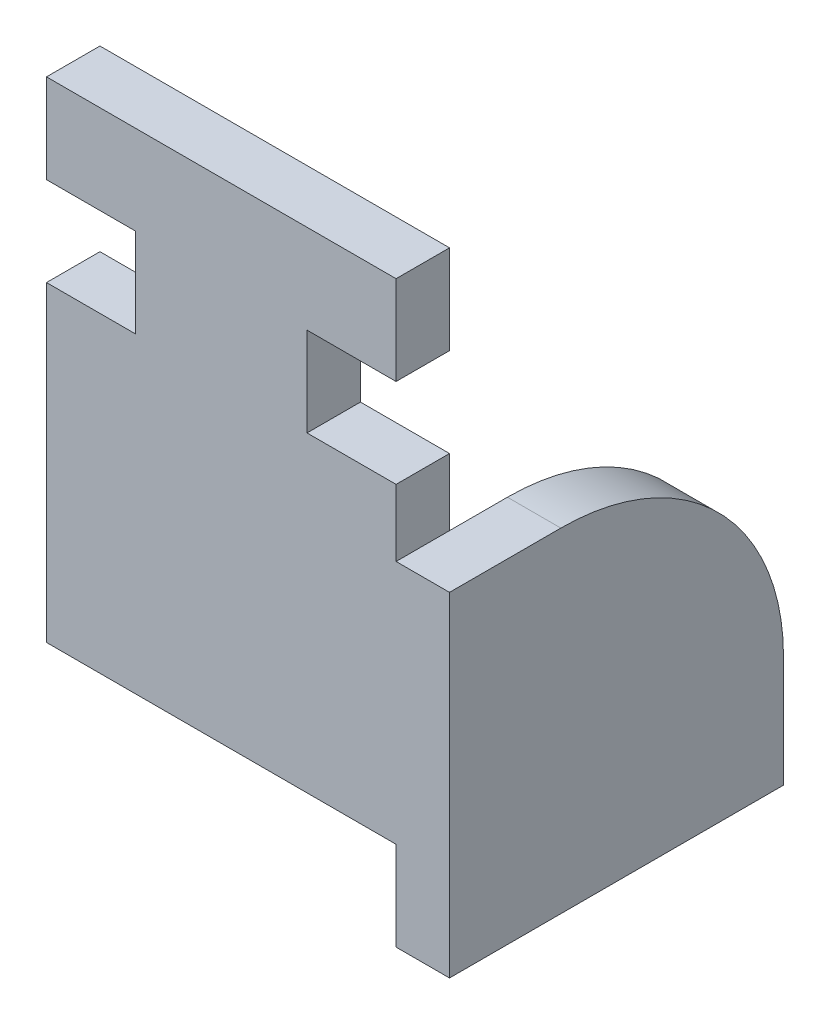
SolidWorks part; units mm, degrees
material "PBT General Purpose"
ref_plane "Front Plane" through (0, 0, 0) normal (0, 0, 1) x (1, 0, 0)
ref_plane "Top Plane" through (0, 0, 0) normal (0, 1, 0) x (1, 0, 0)
ref_plane "Right Plane" through (0, 0, 0) normal (1, 0, 0) x (0, 0, -1)
sketch "Sketch1" plane through (0, 0, 0) normal (0, 0, 1) x (1, 0, 0)
  line L0 (0, 0) -> (0, 1.4)
  line L1 (0, 1.4) -> (0.4, 1.4)
  line L2 (0.4, 1.4) -> (0.4, 1.8)
  line L3 (0.4, 1.8) -> (0, 1.8)
  line L4 (0, 1.8) -> (0, 2.2)
  line L5 (0, 2.2) -> (1.57, 2.2)
  line L6 (1.57, 2.2) -> (1.57, 1.8)
  line L7 (1.57, 1.8) -> (1.17, 1.8)
  line L8 (1.17, 1.8) -> (1.17, 1.4)
  line L9 (1.17, 1.4) -> (1.57, 1.4)
  line L10 (1.57, 1.4) -> (1.57, 0)
  line L11 (1.57, 0) -> (0, 0)
  dimension "D1" = 0.4
  dimension "D2" = 0.4
  dimension "D3" = 0.77
  dimension "D4" = 0.4
  dimension "D5" = 0.4
  dimension "D6" = 1.4
  dimension "D7" = 0.4
extrude "Boss-Extrude1" add sketch "Sketch1" along normal blind 0.24
sketch "Sketch2" plane through (1.57, 0, 0) normal (1, 0, 0) x (0, 0, -1)
  line L0 (-0.24, 1.4) -> (0, 1.4) construction
  line L1 (-0.24, -0.4) -> (1.26, -0.4)
  line L2 (-0.24, -0.4) -> (-0.24, 1.1)
  line L3 (-0.24, 1.1) -> (1.26, 1.1)
  line L4 (1.26, -0.4) -> (1.26, 1.1)
  line L5 (-0.24, 0) -> (-0.24, 1.4) construction
  point P7 (-0.24, 0)
  point P8 (-0.257, -0.5845)
  point P9 (-0.3447, 1.1)
  dimension "D1" = 0.3
  dimension "D2" = 1.5
  dimension "D3" = 1.5
extrude "Boss-Extrude2" add sketch "Sketch2" along normal blind 0.24 contours L3 L4 L1 L2
fillet "Fillet1" radius 1 1 edges at (1.69, 1.1, -1.26)
